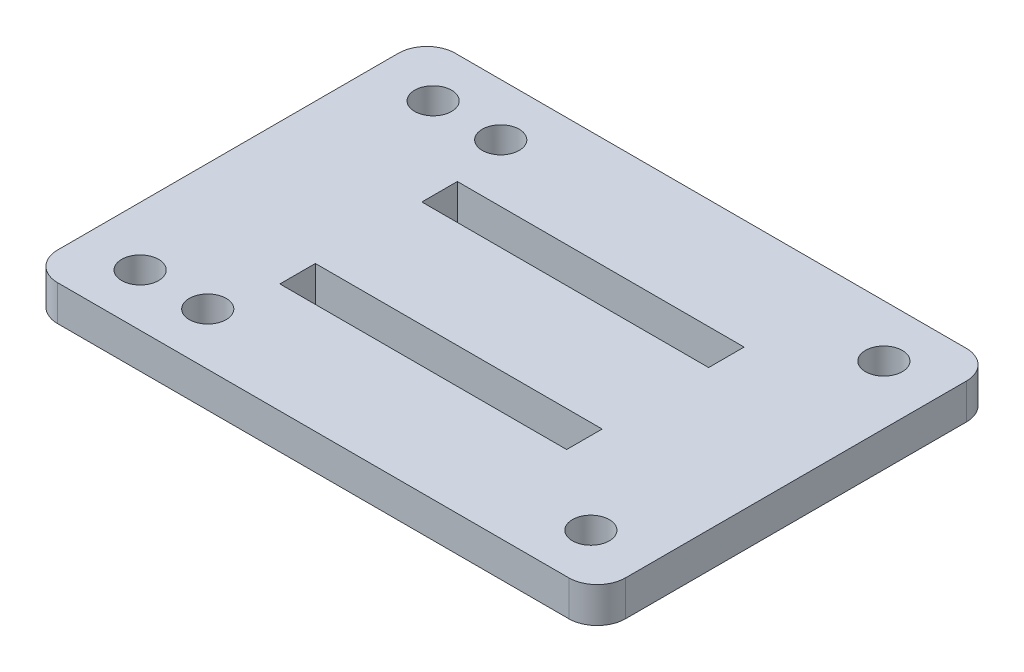
SolidWorks part; units mm, degrees
other "下垫片"
ref_plane "前视基准面" through (0, 0, 0) normal (0, 0, 1) x (1, 0, 0)
ref_plane "上视基准面" through (0, 0, 0) normal (0, 1, 0) x (1, 0, 0)
ref_plane "右视基准面" through (0, 0, 0) normal (1, 0, 0) x (0, 0, -1)
other "Configuration Table"
sketch "草图1" plane through (0, 0, 0) normal (0, 1, 0) x (1, 0, 0)
  line L0 (-89.3251, 0) -> (102.0425, 0) construction
  line L1 (0, 56.7239) -> (0, -62.578) construction
  line L2 (-20.2, -7.5) -> (20.2, -7.5)
  line L3 (-20.2, 12.5) -> (20.2, 12.5)
  line L4 (-20.2, 12.5) -> (-20.2, 7.5)
  line L5 (-20.2, 7.5) -> (20.2, 7.5)
  line L6 (20.2, 12.5) -> (20.2, 7.5)
  line L7 (-20.2, 12.5) -> (20.2, 7.5) construction
  line L8 (-20.2, 7.5) -> (20.2, 12.5) construction
  line L9 (20.2, -12.5) -> (20.2, -7.5)
  line L10 (-20.2, -12.5) -> (20.2, -12.5)
  line L11 (-20.2, -12.5) -> (-20.2, -7.5)
  circle A0 centre (-31.75, 20.6375) radius 2.6
  circle A4 centre (31.75, 20.6375) radius 2.6
  circle A5 centre (31.75, -20.6375) radius 2.6
  circle A6 centre (-31.75, -20.6375) radius 2.6
  circle A7 centre (-22.225, 20.6375) radius 2.6
  circle A8 centre (-22.225, -20.6375) radius 2.6
  point P13 (0, 10)
  dimension "D5" = 5.2
  dimension "D9" = 5.2
  dimension "D7" = 10
  dimension "D6" = 5.2
  dimension "D1" = 40.4
  dimension "D2" = 31.75
  dimension "D3" = 5
  dimension "D4" = 20.6375
  dimension "D8" = 5
  dimension "D10" = 40.4
  dimension "D11" = 8.1375
  dimension "D12" = 31.75
  dimension "D13" = 9.525
sketch "草图3" plane through (0, 0, 0) normal (0, 1, 0) x (1, 0, 0)
  line L1 (-40, -28) -> (40, -28)
  line L2 (-40, -28) -> (-40, 28)
  line L3 (-40, 28) -> (40, 28)
  line L4 (40, -28) -> (40, 28)
  line L5 (-40, -28) -> (40, 28) construction
  line L6 (-40, 28) -> (40, -28) construction
  point P0 (0, 0)
  dimension "D1" = 56
  dimension "D2" = 80
extrude "凸台-拉伸1" add sketch "草图3" along normal blind 5
extrude "切除-拉伸1" cut sketch "草图1" along normal up to surface (5 mm away) up to face at (0, 5, 0)
fillet "圆角2" radius 4 4 edges at (-40, 2.5, -28) (40, 2.5, -28) (40, 2.5, 28) (-40, 2.5, 28)
